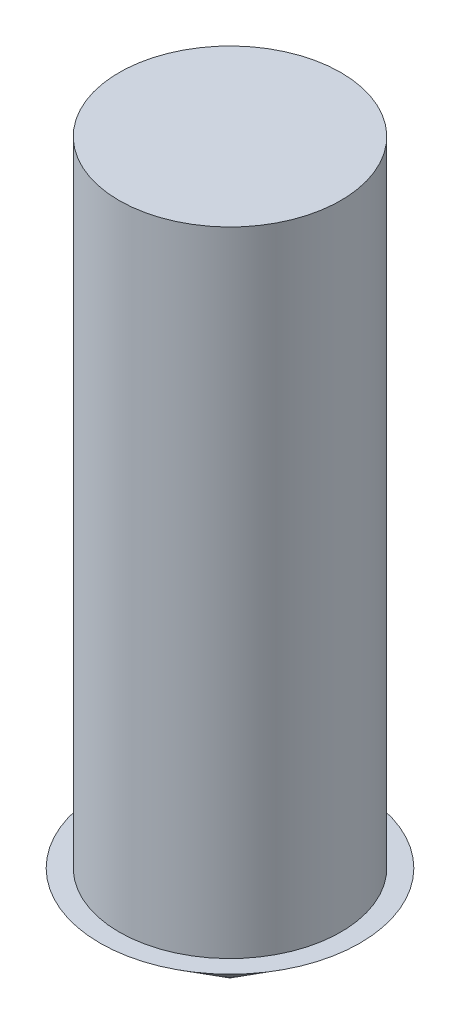
SolidWorks part; units mm, degrees
ref_plane "Front Plane" through (0, 0, 0) normal (0, 0, 1) x (1, 0, 0)
ref_plane "Top Plane" through (0, 0, 0) normal (0, 1, 0) x (1, 0, 0)
ref_plane "Right Plane" through (0, 0, 0) normal (1, 0, 0) x (0, 0, -1)
sketch "Sketch1" plane through (0, 0, 0) normal (0, 0, 1) x (1, 0, 0)
  line L0 (0, 9.9736) -> (0, 25)
  line L1 (17.5, 25) -> (20.52, 25)
  line L3 (0, 25) -> (0, 125)
  line L4 (0, 125) -> (17.5, 125)
  line L5 (17.5, 125) -> (17.5, 25)
  line L6 (20.52, 25) -> (0, 9.9736)
revolve "Revolve1" add sketch "Sketch1" angle 360 about L3
